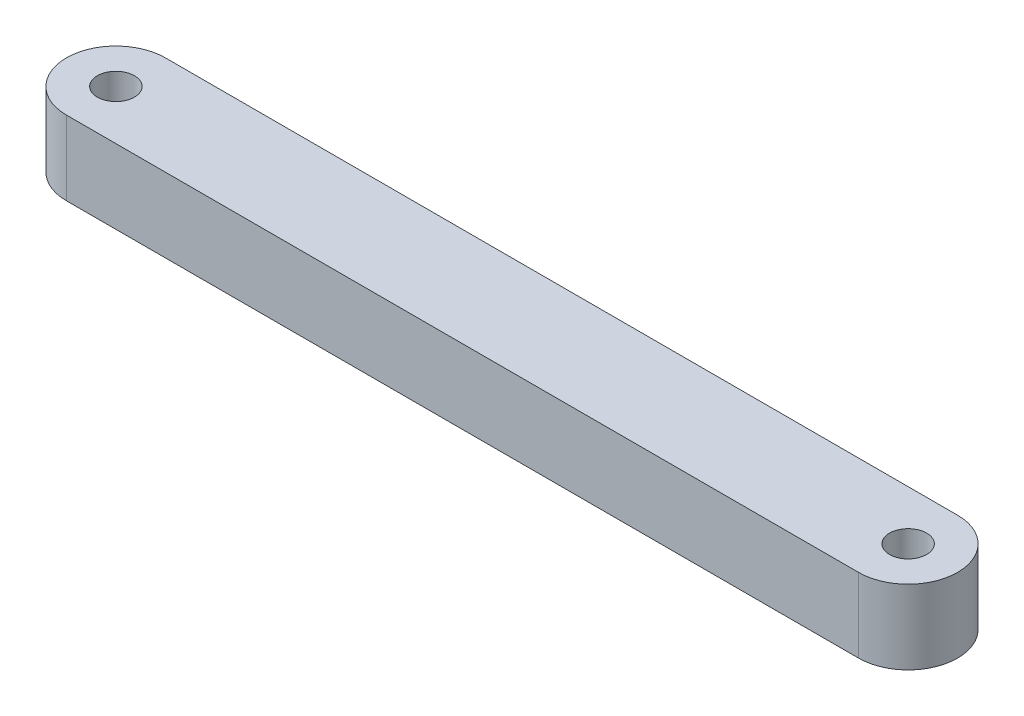
SolidWorks part; units mm, degrees
material "ABS"
ref_plane "Front Plane" through (0, 0, 0) normal (0, 0, 1) x (1, 0, 0)
ref_plane "Top Plane" through (0, 0, 0) normal (0, 1, 0) x (1, 0, 0)
ref_plane "Right Plane" through (0, 0, 0) normal (1, 0, 0) x (0, 0, -1)
sketch "Sketch1" plane through (0, 0, 0) normal (0, 1, 0) x (1, 0, 0)
  line L1 (-80, 10) -> (80, 10)
  line L3 (-80, -10) -> (80, -10)
  line L5 (-80, 10) -> (80, -10) construction
  line L6 (-80, -10) -> (80, 10) construction
  arc A0 (80, 10) -> (80, -10) centre (80, 0) cw
  arc A1 (-80, 10) -> (-80, -10) centre (-80, 0) ccw
  point P0 (0, 0)
  dimension "D1" = 160
  dimension "D2" = 20
extrude "Boss-Extrude1" add sketch "Sketch1" along normal blind 15
sketch "Sketch6" plane through (0, 15, 0) normal (0, 1, 0) x (1, 0, 0)
  circle A0 centre (80, 0) radius 3.75
  dimension "D1" = 7.5
extrude "Cut-Extrude3" cut sketch "Sketch6" against normal blind 10
sketch "Sketch8" plane through (0, 15, 0) normal (0, 1, 0) x (1, 0, 0)
  circle A0 centre (-80, 0) radius 3.75
  dimension "D1" = 7.5
extrude "Cut-Extrude4" cut sketch "Sketch8" against normal blind 10
